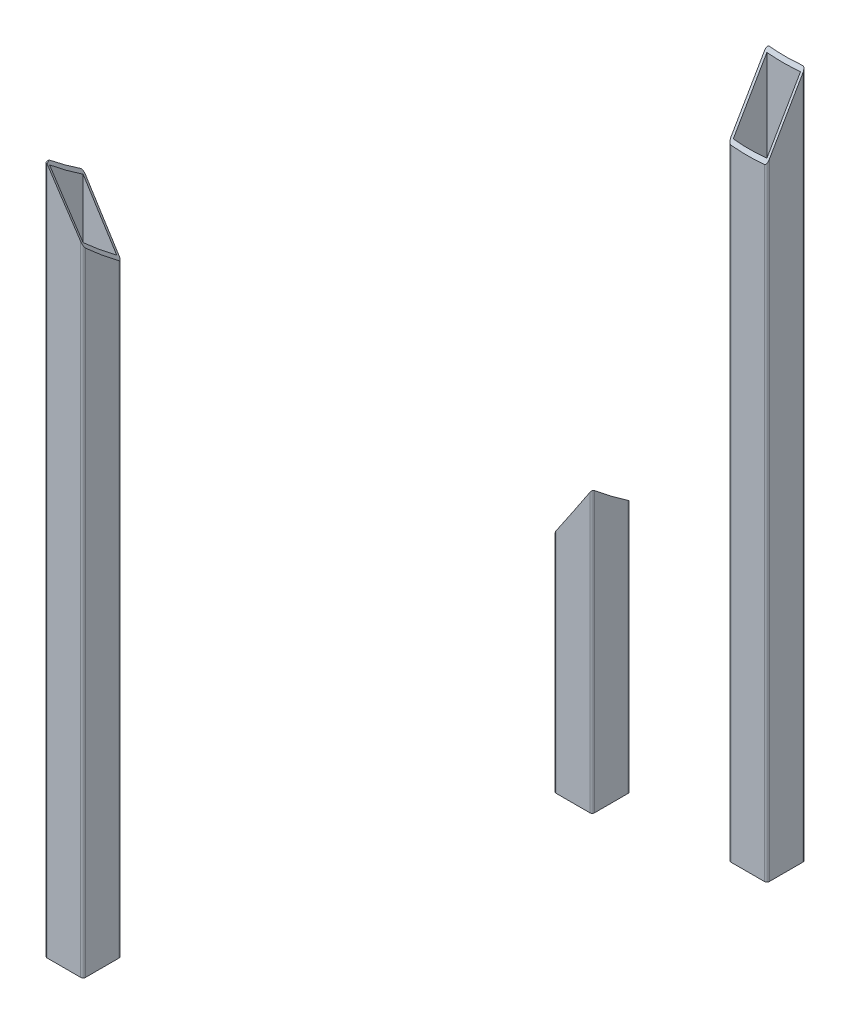
SolidWorks part; units mm, degrees
material "Acero galvanizado"
ref_plane "Front" through (0, 0, 0) normal (0, 0, 1) x (1, 0, 0)
ref_plane "Top" through (0, 0, 0) normal (0, 1, 0) x (1, 0, 0)
ref_plane "Right" through (0, 0, 0) normal (1, 0, 0) x (0, 0, -1)
sketch3d "Croquis3D1"
  line L0 (0, 0, 0) -> (0, 0, 179.5) construction
  line L1 (0, 0, 0) -> (0, 0, -179.5) construction
  line L2 (0, 0, 0) -> (180.5, 0, 0)
  line L3 (0, 0, 0) -> (-179.5, 0, 0) construction
  line L4 (0, 0, -179.5) -> (0, 0, -107.658) construction
  line L5 (0, 0, -179.5) -> (0, 0, -192.7) construction
  line L6 (0, 0, 0) -> (-171.2405, 0, 88.3741) construction
  line L7 (0, 0, 0) -> (171.9288, 0, 87.0275) construction
  line L8 (-171.2405, 0, 88.3741) -> (-171.2405, -455, 88.3741)
  line L9 (171.9288, 0, 87.0275) -> (171.9288, -455, 87.0275)
  line L10 (0, 0, -192.7) -> (0, -455, -192.7)
  line L12 (13.7318, -455, 87.6483) -> (171.9288, -455, 87.0275)
  line L14 (0, -455, -192.7) -> (170.8284, -455, -193.3704)
  line L15 (170.8284, -455, -193.3704) -> (171.9288, -455, 87.0275)
  line L17 (0, -455, -192.7) -> (171.9288, -455, 87.0275) construction
  line L18 (170.8284, -455, -193.3704) -> (-13.9297, -455, 87.7568) construction
  line L19 (-171.2405, -455, 88.3741) -> (-172.3408, -455, -192.0237)
  line L20 (-171.2405, -455, 88.3741) -> (13.7318, -455, 87.6483)
  line L22 (-172.3408, -455, -192.0237) -> (0, -455, -192.7)
  line L23 (-171.2405, -455, 88.3741) -> (0, -455, -192.7) construction
  line L24 (13.7318, -455, 87.6483) -> (-172.3408, -455, -192.0237) construction
  circle A0 centre (0, 0, 0) radius 179.5 construction
  circle A1 centre (0, 0, 0) radius 192.7 construction
  point P11 (0, 192.7, 0)
  point P17 (0, 179.5, 0)
  point P21 (82.342, -455, -58.7298)
  point P24 (-82.5935, -455, -57.1311)
  dimension "D1" = 385.4
  dimension "D2" = 360
  dimension "D3" = 280.4
  dimension "D5" = 455
other "Tubo cuadrada 1 X 1(1)"
ref_plane "Plano2" through (171.9288, 0, 87.0275) normal (0, -1, 0) x (1, 0, 0)
sketch "Croquis11" plane through (171.9288, 0, 87.0275) normal (0, -1, 0) x (1, 0, 0)
  line L5 (-11.1125, 11.1125) -> (-11.1125, -11.1125)
  line L13 (11.1125, 12.7) -> (-11.1125, 12.7)
  line L14 (12.7, 11.1125) -> (12.7, -11.1125)
  line L15 (11.1125, -12.7) -> (-11.1125, -12.7)
  line L16 (-12.7, 11.1125) -> (-12.7, -11.1125)
  line L17 (12.7, 12.7) -> (-12.7, -12.7) construction
  line L18 (12.7, -12.7) -> (-12.7, 12.7) construction
  line L19 (11.1125, -11.1125) -> (-11.1125, -11.1125)
  line L20 (11.1125, 11.1125) -> (11.1125, -11.1125)
  line L21 (11.1125, 11.1125) -> (-11.1125, 11.1125)
  line L22 (12.7, 12.7) -> (-12.7, 12.7) construction
  line L23 (12.7, 12.7) -> (12.7, -12.7) construction
  line L24 (12.7, -12.7) -> (-12.7, -12.7) construction
  line L25 (-12.7, 12.7) -> (-12.7, -12.7) construction
  arc A8 (11.1125, 12.7) -> (12.7, 11.1125) centre (11.1125, 11.1125) cw
  arc A9 (12.7, -11.1125) -> (11.1125, -12.7) centre (11.1125, -11.1125) cw
  arc A10 (-11.1125, -12.7) -> (-12.7, -11.1125) centre (-11.1125, -11.1125) cw
  arc A11 (-12.7, 11.1125) -> (-11.1125, 12.7) centre (-11.1125, 11.1125) cw
  point P0 (0, 0)
  point P6 (-12.7, 0)
  point P22 (-11.1125, 0)
  point P23 (11.1125, 0)
  point P24 (12.7, 0)
  point P25 (0, 11.1125)
  point P26 (0, 12.7)
  point P27 (0, -11.1125)
  point P28 (0, -12.7)
  point P29 (0, 0)
  dimension "D3" = 1.5875
  dimension "D2" = 1.5875
  dimension "D1" = 25.4
sketch "Croquis12" plane through (0, 0, 0) normal (0, 1, 0) x (1, 0, 0)
  circle A0 centre (-0.441, -1.8252) radius 207.2252
ref_plane "Plano3" through (0, 0, 1.8252) normal (0, 0, 1) x (1, 0, 0)
sketch "Croquis14" plane through (0, -455, 0) normal (0, -1, 0) x (1, 0, 0)
  line L5 (188.224, 102.3575) -> (155.8467, 102.3575)
  line L6 (188.224, 102.3575) -> (188.224, 70.3753)
  line L7 (188.224, 70.3753) -> (155.8467, 70.3753)
  line L8 (155.8467, 102.3575) -> (155.8467, 70.3753)
extrude "Cortar-Extruir1" cut sketch "Croquis14" against normal blind 481
sketch "Croquis16" plane through (0, -192.3, 0) normal (0, 1, 0) x (1, 0, 0)
  line L0 (154.4088, -77.2616) -> (154.4088, -99.4866)
  line L1 (176.6338, -75.6741) -> (154.4088, -75.6741)
  line L2 (178.2213, -77.2616) -> (178.2213, -99.4866)
  line L3 (176.6338, -101.0741) -> (154.4088, -101.0741)
  line L4 (152.8213, -77.2616) -> (152.8213, -99.4866)
  line L5 (178.2213, -75.6741) -> (152.8213, -101.0741) construction
  line L6 (178.2213, -101.0741) -> (152.8213, -75.6741) construction
  line L7 (176.6338, -99.4866) -> (154.4088, -99.4866)
  line L8 (176.6338, -77.2616) -> (176.6338, -99.4866)
  line L9 (176.6338, -77.2616) -> (154.4088, -77.2616)
  line L10 (152.8213, -101.0741) -> (152.8213, 204.7259) construction
  line L11 (429.0213, -101.0741) -> (152.8213, -101.0741) construction
  line L12 (176.6338, -77.2616) -> (154.4088, -99.4866) construction
  arc A0 (176.6338, -75.6741) -> (178.2213, -77.2616) centre (176.6338, -77.2616) cw
  arc A1 (178.2213, -99.4866) -> (176.6338, -101.0741) centre (176.6338, -99.4866) cw
  arc A2 (154.4088, -101.0741) -> (152.8213, -99.4866) centre (154.4088, -99.4866) cw
  arc A3 (152.8213, -77.2616) -> (154.4088, -75.6741) centre (154.4088, -77.2616) cw
  point P0 (165.5213, -88.3741)
  point P6 (152.8213, -88.3741)
  point P22 (154.4088, -88.3741)
  point P23 (176.6338, -88.3741)
  point P24 (178.2213, -88.3741)
  point P25 (165.5213, -77.2616)
  point P26 (165.5213, -75.6741)
  point P27 (165.5213, -99.4866)
  point P28 (165.5213, -101.0741)
  point P29 (165.5213, -88.3741)
  point P34 (165.5213, -88.3741)
  dimension "D2" = 1.5875
  dimension "D1" = 25.4
extrude "Saliente-Extruir1" add sketch "Croquis16" along normal blind 185 separate body
sketch "Croquis13" plane through (0, 0, 1.8252) normal (0, 0, 1) x (1, 0, 0)
  line L0 (0, 0) -> (0, -359.6885)
  line L1 (0, -359.6885) -> (-207.6663, 0)
  line L2 (0, 0) -> (-207.6663, 0)
  line L3 (0, -359.6885) -> (-25.1594, -359.6885)
  dimension "D1" = 30
revolve "Cortar-Revolución1" cut sketch "Croquis13" angle 360 about L0
